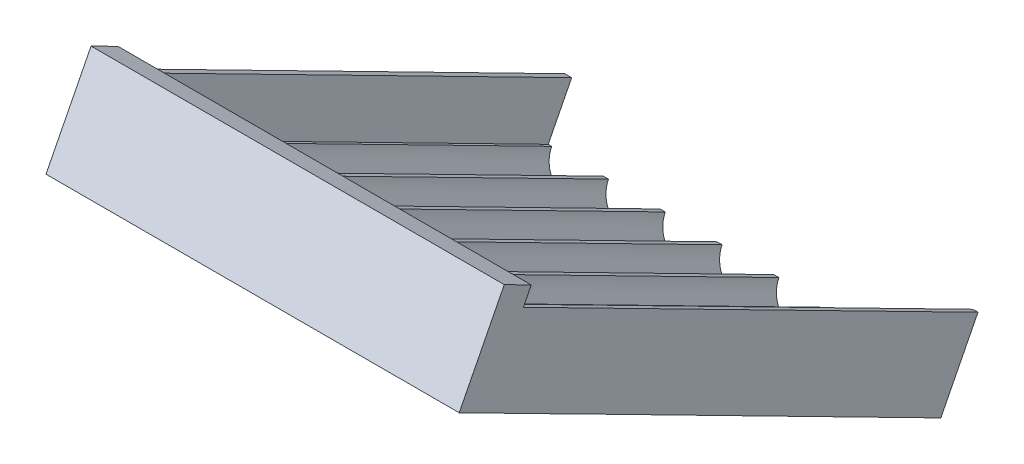
SolidWorks part; units mm, degrees
ref_plane "Front Plane" through (0, 0, 0) normal (0, 0, 1) x (1, 0, 0)
ref_plane "Top Plane" through (0, 0, 0) normal (0, 1, 0) x (1, 0, 0)
ref_plane "Right Plane" through (0, 0, 0) normal (1, 0, 0) x (0, 0, -1)
sketch "Sketch1" plane through (0, 0, 0) normal (1, 0, 0) x (0, 0, -1)
  line L0 (0, 0) -> (-473.1371, 0) construction
  line L1 (54.7142, 100.0614) -> (54.7142, -127.8783) construction
  line L2 (0, -100) -> (-196.2611, 0)
  line L3 (0, -100) -> (54.7142, -127.8783)
  line L4 (54.7142, 100.0614) -> (14.6427, 178.4086) construction
  line L5 (14.6427, 178.4086) -> (-105.3573, 178.4086) construction
  line L6 (-105.3573, 178.4086) -> (-196.2611, 0)
  line L7 (-105.3573, 178.4086) -> (-183.7659, 218.3597)
  line L9 (-183.7659, 218.3597) -> (-314.6208, -38.4574)
  line L10 (-39.9512, -178.4086) -> (-314.6208, -38.4574)
  line L11 (-39.9512, -178.4086) -> (54.7142, -226.3467)
  line L13 (54.7142, -127.8783) -> (1123.922, -672.6669)
  line L14 (54.7142, -226.3467) -> (1123.922, -771.1353)
  line L15 (1123.922, -672.6669) -> (1084.0907, -750.8402)
  dimension "D1" = 120
  dimension "D2" = 1200
  dimension "D5" = 88
  dimension "D6" = 90
  dimension "D7" = 88
  dimension "D8" = 88
extrude "Boss-Extrude1" add sketch "Sketch1" along normal blind 1200 contours L15 L13 L3 L2 L6 L7 L9 L10 L11 L14
sketch "Sketch2" plane through (0, -593.2776, -1164.3729) normal (0, -0.454, -0.891) x (-1, 0, 0)
  line L0 (-600, -89.1007) -> (-600, -164.1007) construction
  line L1 (-1200, -89.1007) -> (0, -89.1007) construction
  line L2 (-675, -89.1007) -> (-525, -89.1007)
  line L3 (-618.2886, -161.8367) -> (-618.2886, -176.8367)
  line L4 (-1200, -176.8367) -> (0, -176.8367) construction
  line L5 (-581.7114, -161.8367) -> (-581.7114, -176.8367)
  line L6 (-618.2886, -176.8367) -> (-581.7114, -176.8367)
  line L7 (-600, -176.8367) -> (-600, -487.0501) construction
  line L8 (-517.5, -89.1007) -> (-517.5, -184.2066) construction
  line L9 (-1200, -89.1007) -> (0, -89.1007) construction
  line L10 (-416.7114, -161.8367) -> (-416.7114, -176.8367)
  line L11 (-416.7114, -176.8367) -> (-453.2886, -176.8367)
  line L12 (-453.2886, -161.8367) -> (-453.2886, -176.8367)
  line L13 (-360, -89.1007) -> (-510, -89.1007)
  line L14 (-352.5, -89.1007) -> (-352.5, -260.0195) construction
  line L15 (-86.7114, -161.8367) -> (-86.7114, -176.8367)
  line L16 (-86.7114, -176.8367) -> (-123.2886, -176.8367)
  line L17 (-123.2886, -161.8367) -> (-123.2886, -176.8367)
  line L18 (-30, -89.1007) -> (-180, -89.1007)
  line L19 (-345, -89.1007) -> (-195, -89.1007)
  line L20 (-251.7114, -161.8367) -> (-251.7114, -176.8367)
  line L21 (-288.2886, -176.8367) -> (-251.7114, -176.8367)
  line L22 (-288.2886, -161.8367) -> (-288.2886, -176.8367)
  line L23 (-1170, -89.1007) -> (-1020, -89.1007)
  line L24 (-1076.7114, -161.8367) -> (-1076.7114, -176.8367)
  line L25 (-1113.2886, -176.8367) -> (-1076.7114, -176.8367)
  line L26 (-1113.2886, -161.8367) -> (-1113.2886, -176.8367)
  line L27 (-911.7114, -161.8367) -> (-911.7114, -176.8367)
  line L28 (-911.7114, -176.8367) -> (-948.2886, -176.8367)
  line L29 (-948.2886, -161.8367) -> (-948.2886, -176.8367)
  line L30 (-855, -89.1007) -> (-1005, -89.1007)
  line L31 (-840, -89.1007) -> (-690, -89.1007)
  line L32 (-746.7114, -161.8367) -> (-746.7114, -176.8367)
  line L33 (-783.2886, -176.8367) -> (-746.7114, -176.8367)
  line L34 (-783.2886, -161.8367) -> (-783.2886, -176.8367)
  line L35 (-581.7114, -161.8367) -> (-581.7114, -176.8367)
  line L36 (-618.2886, -161.8367) -> (-618.2886, -176.8367)
  arc A0 (-675, -89.1007) -> (-618.2886, -161.8367) centre (-600, -89.1007) ccw
  arc A1 (-581.7114, -161.8367) -> (-525, -89.1007) centre (-600, -89.1007) ccw
  arc A2 (-360, -89.1007) -> (-416.7114, -161.8367) centre (-435, -89.1007) cw
  arc A3 (-453.2886, -161.8367) -> (-510, -89.1007) centre (-435, -89.1007) cw
  arc A4 (-30, -89.1007) -> (-86.7114, -161.8367) centre (-105, -89.1007) cw
  arc A5 (-123.2886, -161.8367) -> (-180, -89.1007) centre (-105, -89.1007) cw
  arc A6 (-251.7114, -161.8367) -> (-195, -89.1007) centre (-270, -89.1007) ccw
  arc A7 (-345, -89.1007) -> (-288.2886, -161.8367) centre (-270, -89.1007) ccw
  arc A8 (-1076.7114, -161.8367) -> (-1020, -89.1007) centre (-1095, -89.1007) ccw
  arc A9 (-1170, -89.1007) -> (-1113.2886, -161.8367) centre (-1095, -89.1007) ccw
  arc A10 (-855, -89.1007) -> (-911.7114, -161.8367) centre (-930, -89.1007) cw
  arc A11 (-948.2886, -161.8367) -> (-1005, -89.1007) centre (-930, -89.1007) cw
  arc A12 (-746.7114, -161.8367) -> (-690, -89.1007) centre (-765, -89.1007) ccw
  arc A13 (-840, -89.1007) -> (-783.2886, -161.8367) centre (-765, -89.1007) ccw
  arc A14 (-525, -89.1007) -> (-581.7114, -161.8367) centre (-600, -89.1007) cw
  arc A15 (-618.2886, -161.8367) -> (-675, -89.1007) centre (-600, -89.1007) cw
  line M30 (0, -89.1007) -> (-1200, -89.1007)
  line M32 (-1200, -176.8367) -> (0, -176.8367)
  dimension "D1" = 150
  dimension "D2" = 15
  dimension "D3" = 7.5
  dimension "D4" = 7.5
extrude "Cut-Extrude1" cut sketch "Sketch2" against normal blind 1200 contours A9 L26 L24 A8 M30 M32 | A11 L29 L27 A10 M32 M30 | A13 L34 L32 A12 M30 M32 | L5 A1 A0 L3 M30 M32 | A3 L12 L10 A2 M32 M30 | A7 L22 L20 A6 M30 M32 | A5 L17 L15 A4 M32 M30
sketch "Sketch4" plane through (0, 0, 0) normal (-1, 0, 0) x (0, 0, 1)
  line L3 (128.1625, 133.651) -> (196.2611, 0)
  line L4 (196.2611, 0) -> (-1123.922, -672.6669)
  line L5 (128.1625, 133.651) -> (196.2611, 0)
  line L7 (-1123.922, -672.6669) -> (196.2611, 0)
  line L8 (-1192.0206, -539.0159) -> (-1123.922, -672.6669)
  line L9 (-1123.922, -672.6669) -> (196.2611, 0)
  line L10 (196.2611, 0) -> (128.1625, 133.651)
  line L11 (128.1625, 133.651) -> (-1192.0206, -539.0159)
  dimension "D1" = 150
  dimension "D2" = 150
extrude "Boss-Extrude2" add sketch "Sketch4" against normal blind 20
sketch "Sketch8" plane through (20, 0, 0) normal (1, 0, 0) x (0, 0, -1)
  line L6 (1192.0206, -539.0159) -> (1123.922, -672.6669) construction
  line L7 (1188.55, -545.8272) -> (1123.922, -672.6669)
ref_plane "Plane1" through (1200, 0, 0) normal (1, 0, 0) x (0, 0, -1)
sketch "Sketch14" plane through (1200, 0, 0) normal (1, 0, 0) x (0, 0, -1)
  line L0 (-196.2611, 0) -> (-128.1625, 133.651)
  line L1 (-105.3573, 178.4086) -> (-196.2611, 0) construction
  line L2 (-128.1625, 133.651) -> (1192.0206, -539.0159)
  line L3 (1192.0206, -539.0159) -> (1123.922, -672.6669) construction
  line L4 (1192.0206, -539.0159) -> (1123.922, -672.6669)
  line L5 (1123.922, -672.6669) -> (-196.2611, 0)
  dimension "D1" = 150
extrude "Boss-Extrude6" add sketch "Sketch14" against normal blind 15
